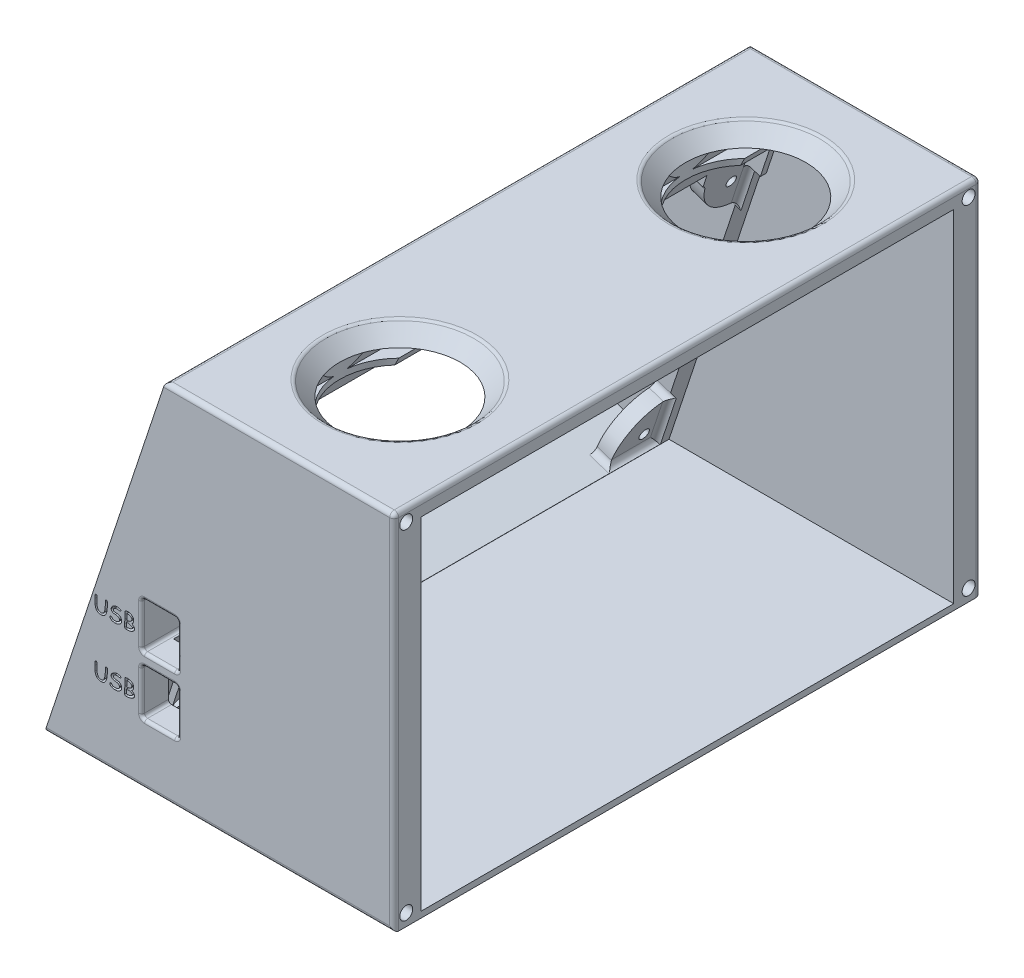
SolidWorks part; units mm, degrees
ref_plane "Front Plane" through (0, 0, 0) normal (0, 0, 1) x (1, 0, 0)
ref_plane "Top Plane" through (0, 0, 0) normal (0, 1, 0) x (1, 0, 0)
ref_plane "Right Plane" through (0, 0, 0) normal (1, 0, 0) x (0, 0, -1)
sketch "Sketch1" plane through (0, 0, 0) normal (0, 0, 1) x (1, 0, 0)
  line L0 (0, 0) -> (-40, 0)
  line L1 (-40, 0) -> (0, 120.5363)
  line L2 (0, 120.5363) -> (0, 0)
  dimension "D1" = 127
  dimension "D2" = 40
extrude "Boss-Extrude1" add sketch "Sketch1" against normal blind 195
sketch "Sketch2" plane through (0, 0, 0) normal (0, 0, 1) x (1, 0, 0)
  line L0 (-40, 0) -> (0, 0) construction
  line L1 (0, 120.5363) -> (76.2, 120.5363)
  line L2 (0, 120.5363) -> (0, 0)
  line L3 (0, 0) -> (76.2, 0)
  line L4 (76.2, 120.5363) -> (76.2, 0)
  dimension "D1" = 76.2
extrude "Boss-Extrude2" add sketch "Sketch2" against normal up to surface (195 mm away) up to face at (-13.3333, 40.1788, -195)
sketch "Sketch3" plane through (-36.032, 11.9572, 0) normal (-0.9491, 0.315, 0) x (0, 0, 1)
  line L0 (-195, 50.9016) -> (0, 50.9016) construction
  line L1 (-180.05, 101.9516) -> (-14.95, 101.9516)
  line L2 (-180.05, 101.9516) -> (-180.05, -0.1484)
  line L3 (-180.05, -0.1484) -> (-14.95, -0.1484)
  line L4 (-14.95, 101.9516) -> (-14.95, -0.1484)
  line L5 (-195, 114.4016) -> (-195, -12.5984) construction
  line L6 (0, 114.4016) -> (0, -12.5984) construction
  line L7 (-97.5, 114.4016) -> (-97.5, -12.5984) construction
  line L8 (-195, 114.4016) -> (0, 114.4016) construction
  line L9 (-195, -12.5984) -> (0, -12.5984) construction
  line L10 (-180.05, 50.9016) -> (-14.95, 50.9016) construction
  point P18 (-97.5, 50.9016)
  point P19 (-97.5, 50.9016)
  dimension "D1" = 165.1
  dimension "D2" = 102.1
extrude "Cut-Extrude1" cut sketch "Sketch3" against normal blind 25.08
sketch "Sketch4" plane through (0, 0, 0) normal (0, 0, 1) x (1, 0, 0)
  line L0 (0, 120.5363) -> (0, 0) construction
ref_plane "Plane1" through (0, 0, 0) normal (-1, 0, 0) x (0, 0, 1)
sketch "Sketch5" plane through (76.2, 0, 0) normal (1, 0, 0) x (0, 0, -1)
  line L0 (13, 0) -> (13, 107.5363)
  line L1 (195, 0) -> (0, 0) construction
  line L2 (13, 107.5363) -> (182, 107.5363)
  line L3 (182, 107.5363) -> (182, 0)
  line L4 (182, 0) -> (13, 0)
  line L5 (0, 120.5363) -> (0, 0) construction
  line L6 (195, 0) -> (195, 120.5363) construction
  line L7 (195, 120.5363) -> (0, 120.5363) construction
  dimension "D1" = 13
  dimension "D2" = 13
  dimension "D3" = 13
extrude "Cut-Extrude2" [suppressed] cut sketch "Sketch5" against normal up to surface (101.6 mm away)
ref_plane "Plane2" through (-21.9852, 7.2958, 0) normal (-0.9491, 0.315, 0) x (0, 0, 1)
sketch "Sketch7" plane through (-21.9852, 7.2958, 0) normal (-0.9491, 0.315, 0) x (0, 0, 1)
  line L0 (-180.05, 50.9016) -> (-14.95, 50.9016) construction
  line L1 (-180.05, 101.9516) -> (-180.05, -0.1484) construction
  line L2 (-14.95, -0.1484) -> (-14.95, 101.9516) construction
  line L3 (-97.5, 101.9516) -> (-97.5, -0.1484) construction
  line L4 (-14.95, 101.9516) -> (-180.05, 101.9516) construction
  line L5 (-180.05, -0.1484) -> (-14.95, -0.1484) construction
  line L6 (-180.05, 86.9516) -> (-180.05, 101.9516)
  line L7 (-180.05, 101.9516) -> (-180.05, -0.1484) construction
  line L8 (-180.05, 101.9516) -> (-165.05, 101.9516)
  line L9 (-180.05, 101.9516) -> (-169.4434, 91.345) construction
  line L10 (-14.95, 101.9516) -> (-25.5566, 91.345) construction
  line L11 (-14.95, 101.9516) -> (-29.95, 101.9516)
  line L12 (-14.95, 86.9516) -> (-14.95, 101.9516)
  line L13 (-14.95, -0.1484) -> (-25.5566, 10.4582) construction
  line L14 (-180.05, -0.1484) -> (-169.4434, 10.4582) construction
  line L15 (-14.95, 14.8516) -> (-14.95, -0.1484)
  line L16 (-14.95, -0.1484) -> (-29.95, -0.1484)
  line L17 (-180.05, -0.1484) -> (-165.05, -0.1484)
  line L18 (-180.05, 14.8516) -> (-180.05, -0.1484)
  arc A0 (-165.05, 101.9516) -> (-180.05, 86.9516) centre (-180.05, 101.9516) cw
  circle A1 centre (-175, 96.9016) radius 1.7
  circle A2 centre (-20, 96.9016) radius 1.7
  arc A3 (-29.95, 101.9516) -> (-14.95, 86.9516) centre (-14.95, 101.9516) ccw
  arc A4 (-29.95, -0.1484) -> (-14.95, 14.8516) centre (-14.95, -0.1484) cw
  circle A5 centre (-20, 4.9016) radius 1.7
  circle A6 centre (-175, 4.9016) radius 1.7
  arc A7 (-165.05, -0.1484) -> (-180.05, 14.8516) centre (-180.05, -0.1484) ccw
  dimension "D2" = 3.4
  dimension "D3" = 5.05
  dimension "D4" = 5.05
  dimension "D1" = 15
extrude "Boss-Extrude3" add sketch "Sketch7" against normal blind 5
ref_plane "Plane3" through (-12.2284, 4.058, 0) normal (-0.9491, 0.315, 0) x (0, 0, 1)
sketch "Sketch8" plane through (0, 0, 0) normal (0, 0, 1) x (1, 0, 0)
  line L0 (-11.9158, 5) -> (76.2, 5)
  line L1 (5.0944, 56.2588) -> (-29.5513, -48.1427) construction
  line L2 (76.2, 0) -> (76.2, 120.5363) construction
  line L3 (-11.9158, 5) -> (23.7701, 112.5363)
  line L4 (23.7701, 112.5363) -> (76.2, 112.5363)
  line L5 (76.2, 112.5363) -> (76.2, 5)
  line L6 (76.2, 120.5363) -> (0, 120.5363) construction
  line L7 (-40, 0) -> (76.2, 0) construction
  dimension "D1" = 8
  dimension "D2" = 5
extrude "Cut-Extrude3" cut sketch "Sketch8" against normal up to surface (195 mm away) up to face at (28.1, 60.2682, -195)
fillet "Fillet1" radius 2 16 edges at (-17.2865, 5.5801, -172.55) (-14.9243, 12.6984, -180.05) (-17.2865, 5.5801, -22.45) (-14.9243, 12.6984, -14.95) (12.5088, 95.3654, -180.05) (14.871, 102.4837, -172.55) (14.871, 102.4837, -22.45) (12.5088, 95.3654, -14.95) (7.7738, 89.0346, -180.05) (12.4983, 103.2711, -165.05) (-19.6592, 6.3675, -165.05) (-14.9348, 20.6041, -180.05) (-19.6592, 6.3675, -29.95) (-14.9348, 20.6041, -14.95) (7.7738, 89.0346, -14.95) (12.4983, 103.2711, -29.95)
chamfer "Chamfer1" [suppressed] distance 2 angle 45
sketch "Sketch9" plane through (0, 0, 0) normal (0, 0, 1) x (1, 0, 0)
  line L0 (76.2, 112.5363) -> (23.7701, 112.5363)
  line L1 (23.7701, 112.5363) -> (-11.9158, 5)
  line L2 (-11.9158, 5) -> (76.2, 5)
  line L3 (76.2, 5) -> (76.2, 112.5363)
  line L8 (20.9778, 55.9061) -> (20.9778, 5) construction
  dimension "D5" = 55.2222
  dimension "D8" = 50.9061
extrude "Boss-Extrude4" add sketch "Sketch9" against normal up to surface (14.95 mm away) up to face at (-5.0277, 51.2545, -14.95)
sketch "Sketch10" plane through (0, 0, 0) normal (0, 0, 1) x (1, 0, 0)
  line L0 (-7.8, 54.48) -> (4.2, 54.48)
  line L1 (-7.8, 54.48) -> (-7.8, 39.24)
  line L2 (-7.8, 39.24) -> (4.2, 39.24)
  line L3 (4.2, 54.48) -> (4.2, 39.24)
  line L8 (-7.8, 54.48) -> (-7.8, 0) construction
  line L10 (-40, 0) -> (76.2, 0) construction
  line L11 (76.2, 0) -> (76.2, 120.5363) construction
  line L14 (-7.8, 35.24) -> (4.2, 35.24)
  line L15 (-7.8, 35.24) -> (-7.8, 20)
  line L16 (-7.8, 20) -> (4.2, 20)
  line L17 (4.2, 35.24) -> (4.2, 20)
  dimension "D1" = 12
  dimension "D2" = 4
  dimension "D3" = 20
  dimension "D4" = 15.24
  dimension "D5" = 84
extrude "Cut-Extrude4" cut sketch "Sketch10" against normal up to surface (14.95 mm away) up to face at (6.9256, 56.0239, -14.95)
fillet "Fillet2" radius 1 24 edges at (-1.8, 39.24, -14.95) (-1.8, 39.24, 0) (4.2, 46.86, 0) (4.2, 39.24, -7.475) (4.2, 46.86, -14.95) (-1.8, 54.48, 0) (4.2, 54.48, -7.475) (-1.8, 54.48, -14.95) (-7.8, 39.24, -7.475) (-7.8, 46.86, 0) (-7.8, 54.48, -7.475) (-7.8, 46.86, -14.95) (-1.8, 20, -14.95) (-1.8, 20, 0) (-1.8, 35.24, 0) (-1.8, 35.24, -14.95) (4.2, 35.24, -7.475) (4.2, 27.62, 0) (4.2, 20, -7.475) (4.2, 27.62, -14.95) (-7.8, 20, -7.475) (-7.8, 27.62, 0) (-7.8, 35.24, -7.475) (-7.8, 27.62, -14.95)
sketch "Sketch12" plane through (0, 5, 0) normal (0, 1, 0) x (1, 0, 0)
  line L0 (76.2, 195) -> (76.2, 0) construction
  line L1 (12.04, 189.4) -> (66.04, 189.4)
  line L2 (12.04, 189.4) -> (12.04, 25.4)
  line L3 (12.04, 25.4) -> (66.04, 25.4)
  line L4 (66.04, 189.4) -> (66.04, 25.4)
  line L5 (76.2, 0) -> (0, 0) construction
  dimension "D1" = 164
  dimension "D2" = 54
  dimension "D3" = 10.16
  dimension "D4" = 25.4
sketch "Sketch13" plane through (0, 120.5363, 0) normal (0, 1, 0) x (1, 0, 0)
  line L0 (38.1, 195) -> (38.1, 0) construction
  line L1 (76.2, 195) -> (0, 195) construction
  line L2 (76.2, 0) -> (0, 0) construction
  circle A0 centre (38.1, 155) radius 20
  circle A1 centre (38.1, 40) radius 20
  dimension "D1" = 40
  dimension "D2" = 40
  dimension "D3" = 40
  dimension "D4" = 40
extrude "Cut-Extrude5" cut sketch "Sketch13" against normal blind 20
chamfer "Chamfer2" distance 5 angle 45 2 edges at (38.1, 120.5363, -20) (38.1, 120.5363, -135)
sketch "Sketch15" plane through (0, 0, -195) normal (0, 0, -1) x (-1, 0, 0)
  line L0 (-76.2, 112.5363) -> (-23.7701, 112.5363)
  line L1 (-23.7701, 112.5363) -> (11.9158, 5)
  line L2 (11.9158, 5) -> (-76.2, 5)
  line L3 (-76.2, 5) -> (-76.2, 112.5363)
extrude "Boss-Extrude5" add sketch "Sketch15" against normal up to surface (14.95 mm away) up to face at (-5.0277, 51.2545, -180.05)
ref_plane "Plane5" [suppressed] through (69.85, 0, 0) normal (1, 0, 0) x (0, 0, -1)
sketch "Sketch16" [suppressed] plane through (69.85, 0, 0) normal (1, 0, 0) x (0, 0, -1)
  line L0 (32.766, 105.0702) -> (12.7, 105.0702)
  line L1 (215.9, 105.0702) -> (12.7, 105.0702) construction
  line L2 (12.7, 105.0702) -> (12.7, 85.0042)
  line L3 (12.7, 5.1605) -> (12.7, 105.0702) construction
  line L4 (12.7, 105.0702) -> (26.8888, 90.8813) construction
  line L5 (114.3, 105.0702) -> (114.3, 0) construction
  line L6 (228.6, 0) -> (0, 0) construction
  line L7 (12.7, 55.1153) -> (215.9, 55.1153) construction
  line L8 (12.7, 105.0702) -> (12.7, 5.1605) construction
  line L9 (215.9, 105.0702) -> (215.9, 5.1605) construction
  line L10 (215.9, 105.0702) -> (201.7112, 90.8813) construction
  line L11 (215.9, 105.0702) -> (215.9, 85.0042)
  line L12 (195.834, 105.0702) -> (215.9, 105.0702)
  line L13 (215.9, 5.1605) -> (201.7112, 19.3494) construction
  line L14 (12.7, 5.1605) -> (26.8888, 19.3494) construction
  line L15 (195.834, 5.1605) -> (215.9, 5.1605)
  line L16 (215.9, 5.1605) -> (215.9, 25.2265)
  line L17 (12.7, 5.1605) -> (12.7, 25.2265)
  line L18 (32.766, 5.1605) -> (12.7, 5.1605)
  line L19 (215.9, 5.1605) -> (215.9, 105.0702) construction
  arc A0 (12.7, 85.0042) -> (32.766, 105.0702) centre (12.7, 105.0702) ccw
  circle A1 centre (19.7944, 97.9757) radius 2.15
  circle A2 centre (208.8056, 97.9757) radius 2.15
  arc A3 (215.9, 85.0042) -> (195.834, 105.0702) centre (215.9, 105.0702) cw
  arc A4 (215.9, 25.2265) -> (195.834, 5.1605) centre (215.9, 5.1605) ccw
  circle A5 centre (208.8056, 12.2549) radius 2.15
  circle A6 centre (19.7944, 12.2549) radius 2.15
  arc A7 (12.7, 25.2265) -> (32.766, 5.1605) centre (12.7, 5.1605) cw
  dimension "D3" = 4.3
  dimension "D1" = 20.066
  dimension "D2" = 20.066
extrude "Boss-Extrude6" [suppressed] add sketch "Sketch16" against normal blind 5
sketch "Sketch17" plane through (76.2, 0, 0) normal (1, 0, 0) x (0, 0, -1)
  line L0 (0, 116.5363) -> (195, 116.5363) construction
  line L1 (0, 120.5363) -> (0, 0) construction
  line L2 (195, 0) -> (195, 120.5363) construction
  line L3 (191, 120.5363) -> (191, 0) construction
  line L4 (195, 120.5363) -> (0, 120.5363) construction
  line L5 (195, 0) -> (0, 0) construction
  line L6 (4, 120.5363) -> (4, 0) construction
  line L7 (0, 4) -> (195, 4) construction
  circle A0 centre (4, 116.5363) radius 2.15
  circle A1 centre (191, 116.5363) radius 2.15
  circle A2 centre (191, 4) radius 2.15
  circle A3 centre (4, 4) radius 2.15
  dimension "D5" = 4.3
  dimension "D1" = 4
  dimension "D2" = 4
  dimension "D3" = 4
  dimension "D4" = 4
extrude "Cut-Extrude6" cut sketch "Sketch17" against normal blind 8
sketch "Sketch19" plane through (0, 120.5363, 0) normal (0, 1, 0) x (1, 0, 0)
  line L0 (46.2, 103.5) -> (46.2, 91.5) construction
  line L1 (76.2, 195) -> (76.2, 0) construction
  line L3 (46.2, 97.5) -> (76.2, 97.5) construction
  line L5 (46.2, 103.5) -> (46.2, 91.5) construction
  line L6 (76.2, 0) -> (0, 0) construction
  line L7 (46.2, 0) -> (46.2, 195) construction
  circle A0 centre (46.2, 110) radius 6.5
  circle A1 centre (46.2, 85) radius 6.5
  point P0 (46.2, 97.5)
  point P12 (46.2, 103.5)
  point P13 (46.2, 91.5)
  point P18 (76.2, 97.5)
  dimension "D2" = 13
  dimension "D3" = 13
  dimension "D5" = 25
  dimension "D1" = 30
extrude "Cut-Extrude7" [suppressed] cut sketch "Sketch19" against normal up to next
fillet "Fillet3" radius 1.5 10 edges at (38.1, 120.5363, -195) (38.1, 120.5363, 0) (76.2, 120.5363, -97.5) (38.1, 120.5363, -15) (38.1, 120.5363, -130) (0, 120.5363, -97.5) (76.2, 60.2682, -195) (76.2, 60.2682, 0) (18.1, 0, -195) (18.1, 0, 0)
sketch "Sketch20" plane through (0, 0, 0) normal (0, 0, 1) x (1, 0, 0)
  text T0 "<b>USB   USB</b>" font "Lucida Sans" height 6
extrude "Cut-Extrude8" [suppressed] cut sketch "Sketch20" against normal blind 4
sketch "Sketch22" plane through (76.2, 0, 0) normal (1, 0, 0) x (0, 0, -1)
  line L0 (180.05, 5) -> (180.05, 112.5363) construction
  line L1 (14.95, 112.5363) -> (180.05, 112.5363)
  line L2 (14.95, 112.5363) -> (14.95, 104.5363)
  line L3 (14.95, 104.5363) -> (180.05, 104.5363)
  line L4 (180.05, 112.5363) -> (180.05, 104.5363)
  dimension "D1" = 8
extrude "Boss-Extrude7" [suppressed] add sketch "Sketch22" against normal up to surface (52.4299 mm away)
sketch "Sketch28" plane through (-36.032, 11.9572, 0) normal (-0.9491, 0.315, 0) x (0, 0, 1)
  line L0 (-14.95, -0.1484) -> (-14.95, 101.9516) construction
  line L1 (-180.05, 101.9516) -> (-14.95, 101.9516)
  line L2 (-180.05, 101.9516) -> (-180.05, 103.9516)
  line L3 (-180.05, 103.9516) -> (-14.95, 103.9516)
  line L4 (-14.95, 101.9516) -> (-14.95, 103.9516)
  dimension "D1" = 2
extrude "Cut-Extrude13" cut sketch "Sketch28" against normal up to surface (14.8 mm away) up to face at (9.0704, 100.879, -20)
sketch "Sketch29" plane through (76.2, 0, 0) normal (1, 0, 0) x (0, 0, -1)
  line L0 (178.05, 88.3743) -> (178.05, 100.5855) construction
  line L1 (16.95, 100.5855) -> (178.05, 100.5855)
  line L2 (16.95, 100.5855) -> (16.95, 110.5855)
  line L3 (16.95, 110.5855) -> (178.05, 110.5855)
  line L4 (178.05, 100.5855) -> (178.05, 110.5855)
  dimension "D1" = 10
extrude "Cut-Extrude14" cut sketch "Sketch29" against normal up to surface (61.9589 mm away)
sketch "Sketch30" plane through (76.2, 0, 0) normal (1, 0, 0) x (0, 0, -1)
  line L1 (30.93, 102.2797) -> (164.07, 102.2797)
  line L2 (30.93, 102.2797) -> (30.93, 106.2797)
  line L3 (30.93, 106.2797) -> (164.07, 106.2797)
  line L4 (164.07, 102.2797) -> (164.07, 106.2797)
  dimension "D1" = 4
extrude "Cut-Extrude15" cut sketch "Sketch30" against normal up to surface (66.6648 mm away)
sketch "Sketch31" plane through (0, 0, 0) normal (0, 0, 1) x (1, 0, 0)
  line L0 (-23.8, 43.24) -> (-7.7493, 43.24) construction
  line L1 (-8.8, 40.24) -> (-8.8, 53.48) construction
  line L2 (3.2, 38.24) -> (-6.8, 38.24) construction
  line L3 (3.2, 19) -> (-6.8, 19) construction
  line L4 (-8.8, 21) -> (-8.8, 34.24) construction
  text T0 "USB" font "Comic Sans MS" height 5
  text T1 "USB" font "Comic Sans MS" height 5
  dimension "D1" = 5
  dimension "D2" = 15
  dimension "D3" = 5
  dimension "D4" = 15
extrude "Cut-Extrude16" cut sketch "Sketch31" against normal blind 4
sketch "Sketch32" plane through (76.2, 0, 0) normal (1, 0, 0) x (0, 0, -1)
  line L1 (14.95, 112.5363) -> (180.05, 112.5363)
  line L2 (14.95, 112.5363) -> (14.95, 5)
  line L3 (14.95, 5) -> (180.05, 5)
  line L4 (180.05, 112.5363) -> (180.05, 5)
  line L5 (8.95, 115.5363) -> (186.05, 115.5363)
  line L6 (8.95, 115.5363) -> (8.95, 2)
  line L7 (8.95, 2) -> (186.05, 2)
  line L8 (186.05, 115.5363) -> (186.05, 2)
  dimension "D1" = 3
  dimension "D2" = 6
  dimension "D3" = 3
  dimension "D4" = 6
extrude "Cut-Extrude17" cut sketch "Sketch32" against normal up to surface (57.993 mm away)
equation "\"1.1811020.5in36in\"=1.1811"
